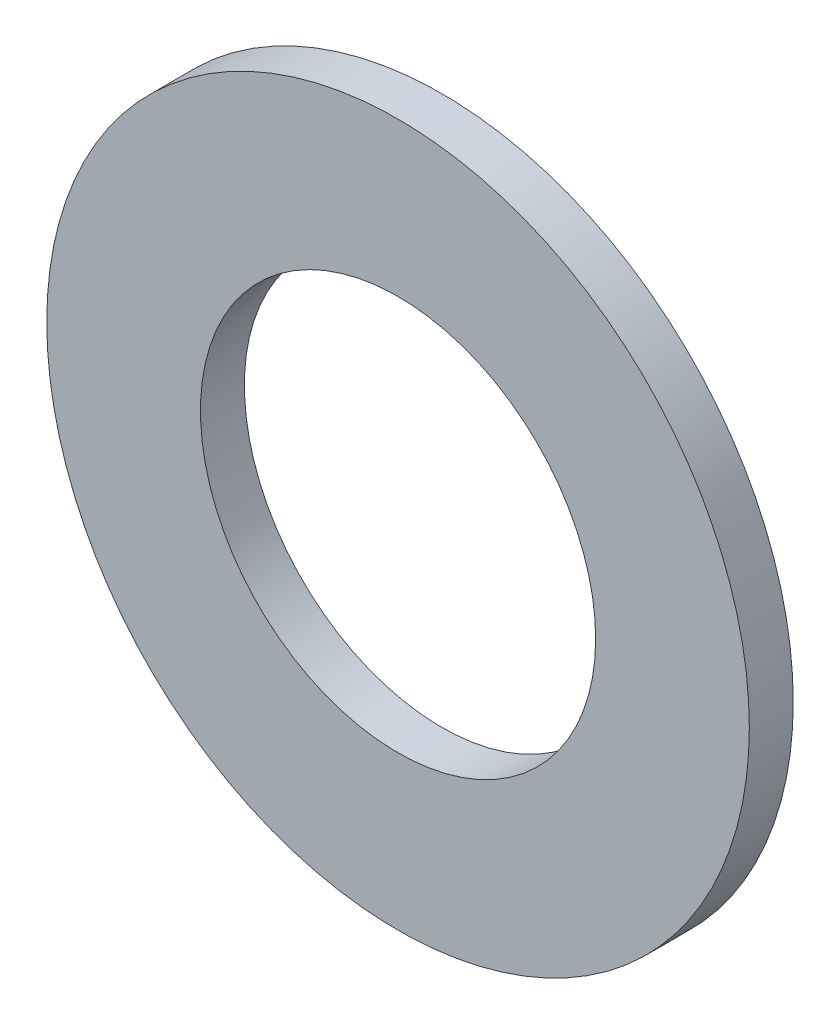
SolidWorks part; units mm, degrees
ref_plane "Front" through (0, 0, 0) normal (0, 0, 1) x (1, 0, 0)
ref_plane "Top" through (0, 0, 0) normal (0, 1, 0) x (1, 0, 0)
ref_plane "Right" through (0, 0, 0) normal (1, 0, 0) x (0, 0, -1)
other "Configuration Table"
sketch "Sketch1" plane through (0, 0, 0) normal (0, 0, 1) x (1, 0, 0)
  circle A0 centre (0, 0) radius 4.5
  circle A1 centre (0, 0) radius 8
  dimension "D1" = 9
  dimension "D2" = 16
extrude "Boss-Extrude1" add sketch "Sketch1" along normal blind 1
